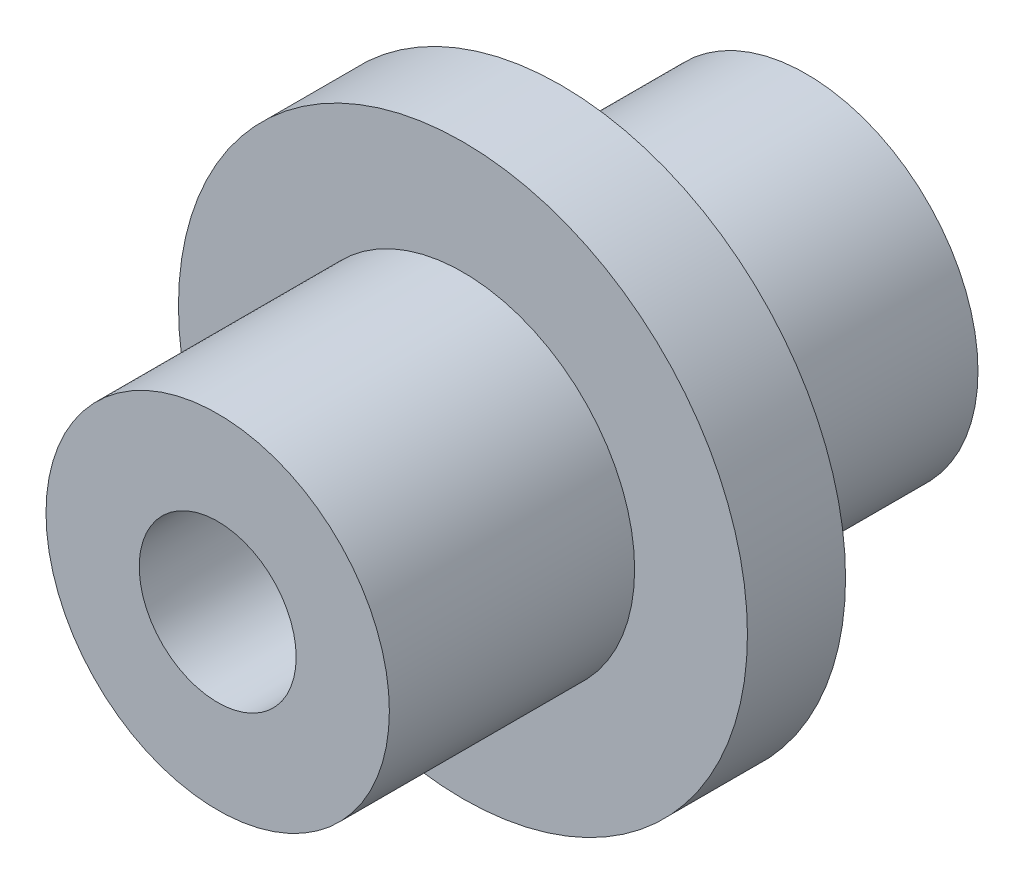
SolidWorks part; units mm, degrees
ref_plane "Front Plane" through (0, 0, 0) normal (0, 0, 1) x (1, 0, 0)
ref_plane "Top Plane" through (0, 0, 0) normal (0, 1, 0) x (1, 0, 0)
ref_plane "Right Plane" through (0, 0, 0) normal (1, 0, 0) x (0, 0, -1)
ref_plane "Plane4" through (0, 0, 33) normal (0, 0, 1) x (1, 0, 0)
sketch "Sketch1" plane through (0, 0, 33) normal (0, 0, 1) x (1, 0, 0)
  circle A0 centre (0, 0) radius 5.8
extrude "Boss-Extrude1" add sketch "Sketch1" against normal blind 2
sketch "Sketch2" plane through (0, 0, 33) normal (0, 0, 1) x (1, 0, 0)
  circle A0 centre (0, 0) radius 3.5
extrude "Boss-Extrude2" add sketch "Sketch2" along normal blind 5 and the other way blind 7
ref_plane "Plane5" through (0, 0, 26) normal (0, 0, 1) x (1, 0, 0)
sketch "Sketch6" plane through (0, 0, 26) normal (0, 0, 1) x (1, 0, 0)
  circle A0 centre (0, 0) radius 1.65
ref_plane "Plane6" through (0, 0, 38) normal (0, 0, 1) x (1, 0, 0)
sketch "Sketch8" plane through (0, 0, 38) normal (0, 0, 1) x (1, 0, 0)
  circle A0 centre (0, 0) radius 1.6
loft "Cut-Loft2" cut profiles "Sketch8", "Sketch6"
